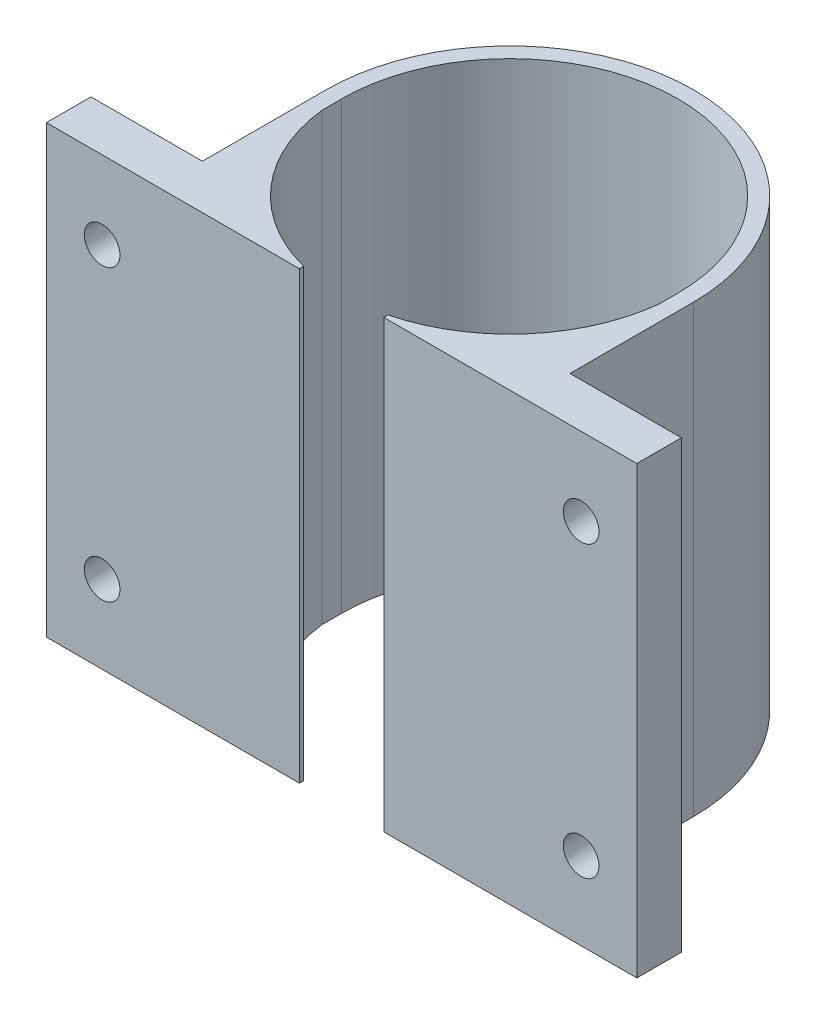
SolidWorks part; units mm, degrees
material "1060 Alloy"
ref_plane "Front Plane" through (0, 0, 0) normal (0, 0, 1) x (1, 0, 0)
ref_plane "Top Plane" through (0, 0, 0) normal (0, 1, 0) x (1, 0, 0)
ref_plane "Right Plane" through (0, 0, 0) normal (1, 0, 0) x (0, 0, -1)
sketch "Sketch3" plane through (0, 0, 0) normal (0, 1, 0) x (1, 0, 0)
  line L0 (-16.5, 0) -> (-16.5, -15.1)
  line L2 (16.5, -15.1) -> (16.5, 0)
  line L3 (15.1, 0) -> (15.1, -15.1)
  line L4 (-15.1, 0) -> (-15.1, -15.1)
  line L5 (0, -15.1) -> (-16.5, -15.1)
  line L6 (-16.5, -15.1) -> (16.5, -15.1)
  arc A0 (15.1, 0) -> (-15.1, 0) centre (0, 0) ccw
  arc A1 (16.5, 0) -> (-16.5, 0) centre (0, 0) ccw
extrude "Boss-Extrude3" add sketch "Sketch3" along normal blind 40
sketch "Sketch8" plane through (16.5, 0, 0) normal (1, 0, 0) x (0, 0, -1)
  line L0 (-15.1, 40) -> (0, 40) construction
  line L1 (-15.1, 0) -> (-11.1, 0)
  line L2 (-15.1, 0) -> (-15.1, 40)
  line L3 (-15.1, 40) -> (-11.1, 40)
  line L4 (-11.1, 0) -> (-11.1, 40)
extrude "Boss-Extrude6" add sketch "Sketch8" along normal blind 10
sketch "Sketch9" plane through (-16.5, 0, 0) normal (-1, 0, 0) x (0, 0, 1)
  line L0 (0, 0) -> (15.1, 0) construction
  line L1 (15.1, 40) -> (11.1, 40)
  line L2 (15.1, 40) -> (15.1, 0)
  line L3 (15.1, 0) -> (11.1, 0)
  line L4 (11.1, 40) -> (11.1, 0)
extrude "Boss-Extrude7" add sketch "Sketch9" along normal blind 10
sketch "Sketch10" plane through (0, 0, 0) normal (0, -1, 0) x (-1, 0, 0)
  line L7 (15.1, -15.1) -> (15.1, -1.7407)
  line L9 (15.1, -15.1) -> (1.7407, -15.1)
  line L10 (3.7913, -15.1) -> (3.7913, -14.7196)
  line L11 (15.1, 0) -> (15.1, -15.1) construction
  line L12 (0, 0) -> (0, 15.1) construction
  line L13 (-3.7913, -15.1) -> (-3.7913, -14.7196)
  line L14 (-15.1, -15.1) -> (-1.7407, -15.1)
  line L15 (-15.1, -15.1) -> (-15.1, -1.7407)
  arc A1 (1.7407, -15.1) -> (15.1, -1.7407) centre (0, 0) ccw
  arc A2 (15.1, 0) -> (-15.1, 0) centre (0, 0) ccw construction
  arc A3 (-1.7407, -15.1) -> (-15.1, -1.7407) centre (0, 0) cw
extrude "Boss-Extrude9" add sketch "Sketch10" against normal blind 40 contours L13 A3 L10 L14 | A1 L10 L9 L13
sketch "Sketch11" plane through (0, 0, 11.1) normal (0, 0, -1) x (-1, 0, 0)
  line L0 (-21.5, 40) -> (-21.5, 0)
  line L1 (-26.5, 40) -> (-16.5, 40) construction
  line L2 (-26.5, 0) -> (-16.5, 0) construction
  line L3 (21.5, 40) -> (21.5, 0)
  line L4 (26.5, 40) -> (16.5, 40) construction
  line L5 (26.5, 0) -> (16.5, 0) construction
  circle A0 centre (-21.5, 33) radius 1.6
  circle A1 centre (-21.5, 7) radius 1.6
  circle A2 centre (21.5, 7) radius 1.6
  circle A3 centre (21.5, 33) radius 1.6
  dimension "D1" = 7
  dimension "D2" = 7
extrude "Cut-Extrude1" cut sketch "Sketch11" against normal blind 40 contours L0 A0 | L0 A1 | L0 A1 | L3 A2 | L3 A2 | L3 A3 | L3 A3
